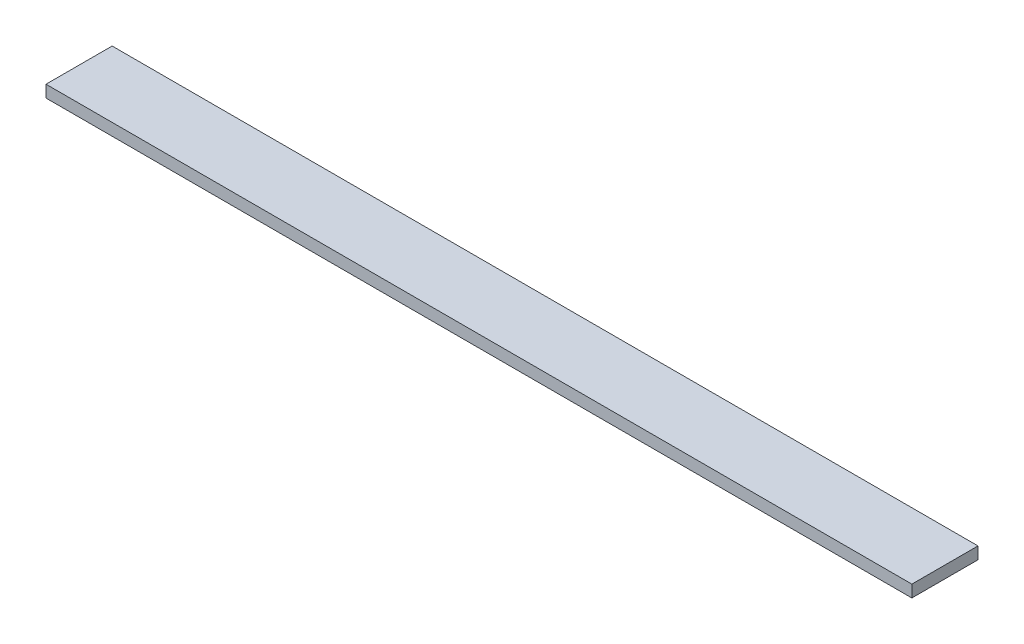
SolidWorks part; units mm, degrees
material "PVC Rigid"
ref_plane "Frontal Plane" through (0, 0, 0) normal (0, 0, 1) x (1, 0, 0)
ref_plane "Horizontal Plane" through (0, 0, 0) normal (0, 1, 0) x (1, 0, 0)
ref_plane "Profile Plane" through (0, 0, 0) normal (1, 0, 0) x (0, 0, -1)
sketch "Sketch1" plane through (0, 0, 0) normal (0, 1, 0) x (1, 0, 0)
  line L1 (-914.4, -69.85) -> (914.4, -69.85)
  line L2 (-914.4, -69.85) -> (-914.4, 69.85)
  line L3 (-914.4, 69.85) -> (914.4, 69.85)
  line L4 (914.4, -69.85) -> (914.4, 69.85)
  line L5 (-914.4, -69.85) -> (914.4, 69.85) construction
  line L6 (-914.4, 69.85) -> (914.4, -69.85) construction
  point P0 (0, 0)
  dimension "D1" = 139.7
  dimension "D2" = 1828.8
extrude "Boss-Extrude1" add sketch "Sketch1" along normal blind 25.4
sketch "Sketch2" plane through (0, 25.4, 0) normal (0, 1, 0) x (1, 0, 0)
  line L0 (-784.4, 69.85) -> (-784.4, -80.15)
  line L1 (914.4, 69.85) -> (-914.4, 69.85) construction
  line L2 (-784.4, -80.15) -> (914.4, -80.15)
  line L3 (914.4, -69.85) -> (914.4, 69.85) construction
  line L4 (914.4, -80.15) -> (914.4, 69.85)
  line L5 (914.4, 69.85) -> (-784.4, 69.85)
  line L6 (-914.4, 69.85) -> (-914.4, -69.85) construction
  dimension "D1" = 130
  dimension "D2" = 150
extrude "Cut-Extrude1" [suppressed] cut sketch "Sketch2" against normal through all
sketch "Sketch3" [suppressed] plane through (0, 12.7, 0) normal (0, 1, 0) x (1, 0, 0)
  line L0 (-720, 155) -> (-850, 155) construction
  line L1 (-830, 135) -> (-740, 135)
  line L2 (-830, 135) -> (-830, 5)
  line L3 (-830, 5) -> (-740, 5)
  line L4 (-740, 135) -> (-740, 5)
  line L5 (-830, 135) -> (-740, 5) construction
  line L6 (-830, 5) -> (-740, 135) construction
  line L7 (-850, 155) -> (-850, -155) construction
  line L8 (-720, 155) -> (-720, 5) construction
  line L9 (-720, 5) -> (850, 5) construction
  point P0 (-785, 70)
  dimension "D1" = 20
  dimension "D2" = 20
  dimension "D3" = 20
extrude "Cut-Extrude2" [suppressed] cut sketch "Sketch3" against normal offset from surface (5 mm away) 5
sketch "Sketch4" plane through (0, 25.4, 0) normal (0, 1, 0) x (1, 0, 0)
  line L0 (-914.4, -69.85) -> (914.4, -69.85) construction
  line L1 (768, 38.45) -> (812, 38.45) construction
  line L2 (0, 219.5854) -> (0, -221.9562) construction
  line L3 (-837.5, -19.05) -> (-757.5, -19.05) construction
  line L4 (757.5, 8.45) -> (822.5, 8.45) construction
  circle A0 centre (-757.5, 8.45) radius 2.5
  circle A1 centre (-822.5, 8.45) radius 2.5
  circle A2 centre (-822.5, -46.55) radius 2.5
  circle A3 centre (-757.5, -46.55) radius 2.5
  circle A4 centre (822.5, -46.55) radius 2.5
  circle A5 centre (822.5, 8.45) radius 2.5
  circle A6 centre (757.5, -46.55) radius 2.5
  circle A7 centre (757.5, 8.45) radius 2.5
  circle A8 centre (768, 38.45) radius 1.25
  circle A9 centre (812, 38.45) radius 1.25
  point P27 (790, 38.45)
  point P28 (790, 8.45)
  dimension "D1" = 5
  dimension "D8" = 2.5
  dimension "D2" = 65
  dimension "D3" = 55
  dimension "D5" = 757.5
  dimension "D4" = 27.5
  dimension "D6" = 50.8
  dimension "D7" = 30
  dimension "D9" = 44
extrude "Cut-Extrude3" [suppressed] cut sketch "Sketch4" against normal blind 10
equation "\"BaseL\"= 6ft"
equation "\"BaseW\"= 5.5in"
equation "\"SlidePlateL\"= 8cm"
equation "\"SlidePlateW\"= 11cm"
equation "\"SlidePlateThickness\"= 5mm"
equation "\"PlateGap\"= 1cm"
equation "\"D1@Sketch1\"=\"BaseW\""
equation "\"D2@Sketch1\"=\"BaseL\""
equation "\"BaseThickness\"= 1in"
equation "\"D1@Boss-Extrude1\"=\"BaseThickness\""
equation "\"D4@Sketch4\"=\"D3@Sketch4\"/2"
